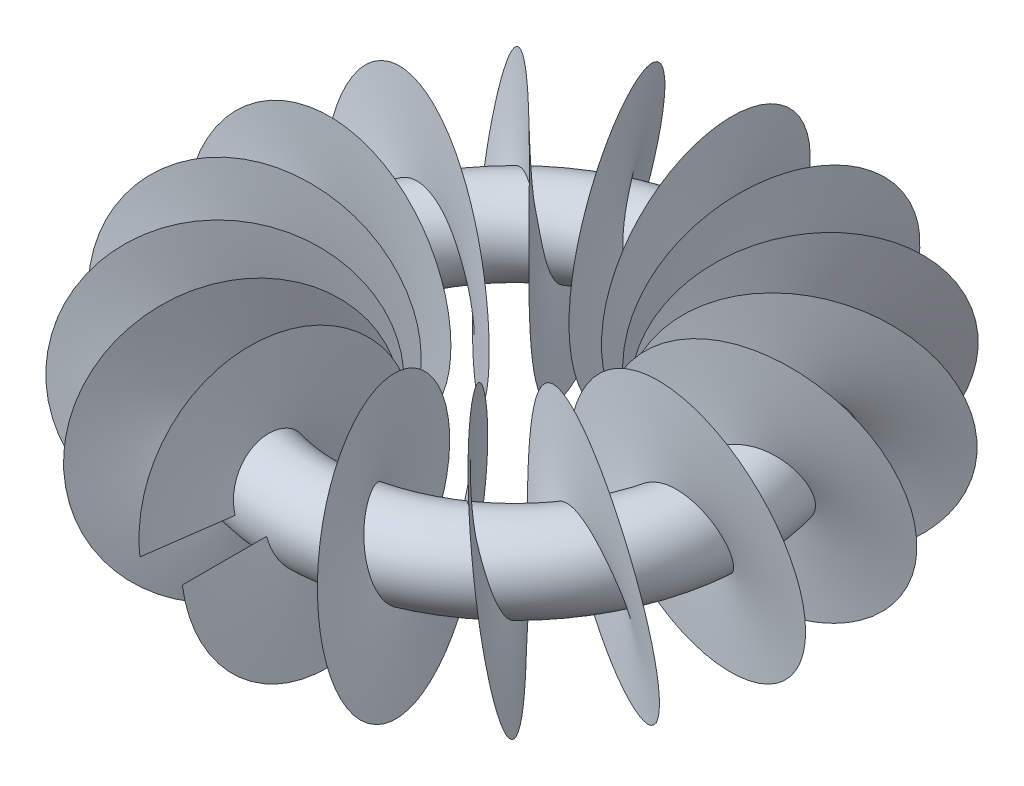
SolidWorks part; units mm, degrees
ref_plane "前视基准面" through (0, 0, 0) normal (0, 0, 1) x (1, 0, 0)
ref_plane "上视基准面" through (0, 0, 0) normal (0, 1, 0) x (1, 0, 0)
ref_plane "右视基准面" through (0, 0, 0) normal (1, 0, 0) x (0, 0, -1)
other "Configuration Table"
sketch "草图1" plane through (0, 0, 0) normal (0, 1, 0) x (1, 0, 0)
  circle A0 centre (0, 0) radius 100
  dimension "D1" = 200
sweep "扫描1" add path "草图1" circular profile diameter 40 parameters "D3"=40
sketch "草图14" plane through (0, 0, 0) normal (0, 1, 0) x (1, 0, 0)
  line L0 (0, 0) -> (0, -229.4485) construction
  line L1 (-11.537, -87.0739) -> (-15.4577, -108.9317) construction
  arc A0 (0, -100) -> (-13.6868, -99.0589) centre (0, 0) ccw
  dimension "D1" = 200
sketch "草图15" plane through (0, 0, 0) normal (0, 1, 0) x (1, 0, 0)
  line L0 (0, -100) -> (0, -160.7307)
  line L1 (0, 0) -> (0, -229.4485) construction
surface "曲面-扫描2" parameters "D0"=6120
sketch3d "3D草图1"
  spline S0 degree 3 number of poles 1791 (0, 0, 120) -> (-16.4242, 0, 118.8707)
  spline S1 degree 3 number of poles 1791 (0, 0, 120) -> (-16.4242, 0, 118.8707)
